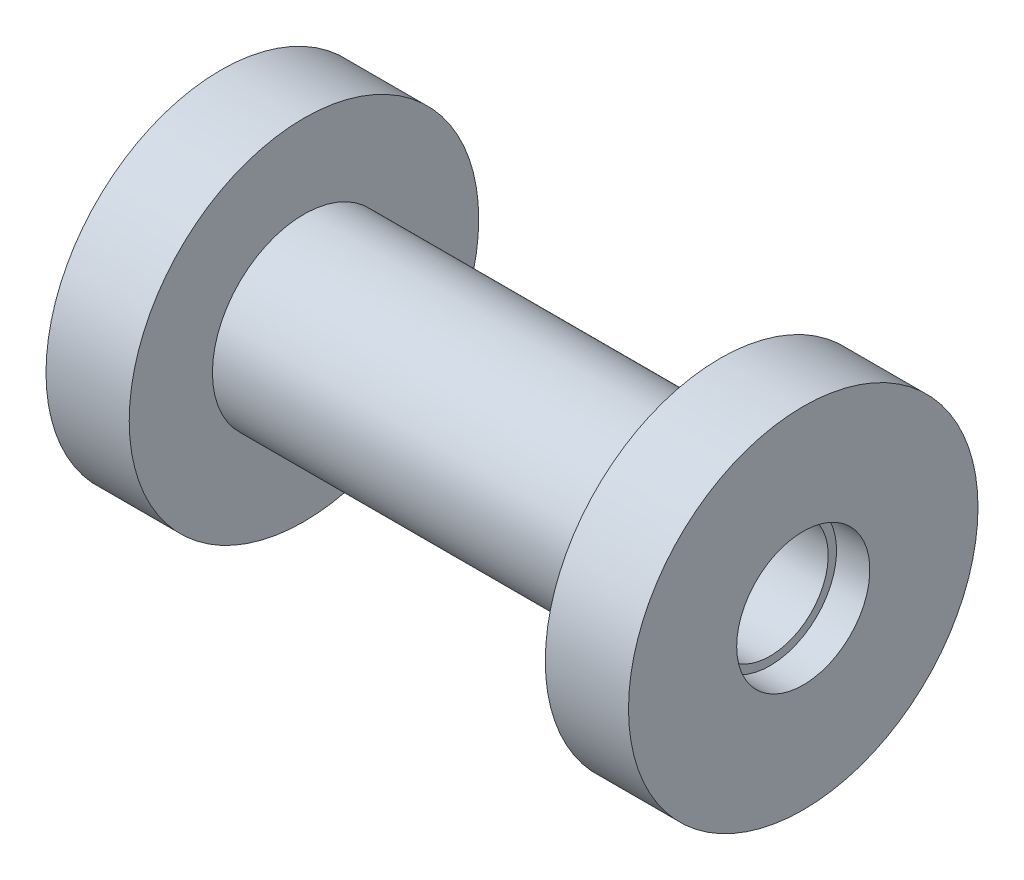
SolidWorks part; units mm, degrees
ref_plane "前视基准面" through (0, 0, 0) normal (0, 0, 1) x (1, 0, 0)
ref_plane "上视基准面" through (0, 0, 0) normal (0, 1, 0) x (1, 0, 0)
ref_plane "右视基准面" through (0, 0, 0) normal (1, 0, 0) x (0, 0, -1)
sketch "草图1" plane through (0, 0, 0) normal (0, 1, 0) x (1, 0, 0)
  line L0 (-74.5155, 0) -> (49.4898, 0) construction
  line L1 (0, 69.6029) -> (0, -37.5757) construction
  line L2 (0, 8) -> (0, 21)
  line L3 (0, 21) -> (10, 21)
  line L4 (10, 21) -> (10, 11)
  line L5 (10, 11) -> (60, 11)
  line L6 (60, 11) -> (60, 21)
  line L7 (60, 21) -> (70, 21)
  line L8 (70, 21) -> (70, 8)
  line L9 (0, 8) -> (4, 8)
  line L10 (4, 8) -> (4, 7)
  line L11 (4, 7) -> (66, 7)
  line L12 (66, 7) -> (66, 8)
  line L13 (66, 8) -> (70, 8)
  point P2 (0, 8)
revolve "旋转1" add sketch "草图1" angle 360 about L0
